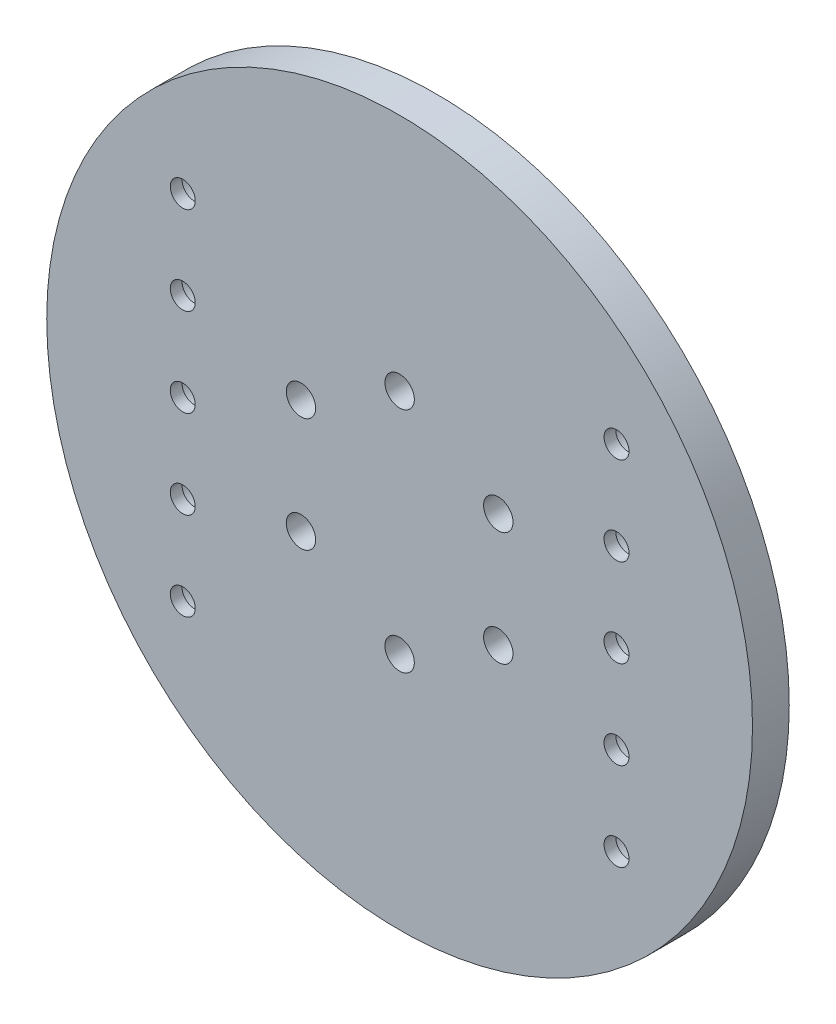
SolidWorks part; units mm, degrees
other "標示1"
sketch "草圖6" plane through (48, -48, 0) normal (0.0015, -0.0177, -0.9998) x (-1, 0.0075, -0.0016)
ref_plane "前基準面" through (0, 0, 0) normal (0, 0, 1) x (1, 0, 0)
ref_plane "上基準面" through (0, 0, 0) normal (0, 1, 0) x (1, 0, 0)
ref_plane "右基準面" through (0, 0, 0) normal (1, 0, 0) x (0, 0, -1)
sketch "草圖1" plane through (0, 0, 0) normal (0, 0, 1) x (1, 0, 0)
  circle A0 centre (0, 0) radius 48
  dimension "D1" = 96
extrude "填料-伸長1" add sketch "草圖1" along normal blind 5
sketch "草圖3" plane through (0, 0, 0) normal (0, 0, -1) x (-1, 0, 0)
  line L0 (-48, 0) -> (48, 0) construction
  line L1 (27, 27.5) -> (27, -27.5)
  line L2 (32, 27.5) -> (27, 27.5)
  line L3 (32, 27.5) -> (32, -27.5)
  line L4 (32, -27.5) -> (27, -27.5)
  line L9 (0, -48) -> (0, 48) construction
  line L14 (29.5, 27.5) -> (29.5, -27.5) construction
  line L15 (-32, -27.5) -> (-27, -27.5)
  line L16 (-32, 27.5) -> (-27, 27.5)
  line L17 (-27, 27.5) -> (-27, -27.5)
  line L18 (-32, 27.5) -> (-32, -27.5)
  circle A0 centre (0, 0) radius 48 construction
  circle A1 centre (29.5, 24) radius 1.25
  circle A2 centre (29.5, 12) radius 1.25
  circle A3 centre (29.5, 0) radius 1.25
  circle A4 centre (29.5, -12) radius 1.25
  circle A5 centre (29.5, -24) radius 1.25
  circle A6 centre (-29.5, 12) radius 1.25
  circle A7 centre (-29.5, 0) radius 1.25
  circle A8 centre (-29.5, -12) radius 1.25
  circle A9 centre (-29.5, -24) radius 1.25
  circle A10 centre (-29.5, 24) radius 1.25
  dimension "D6" = 2.5
  dimension "D8" = 12
  dimension "D1" = 27.5
  dimension "D2" = 5
  dimension "D3" = 3.5
  dimension "D4" = 27.5
  dimension "D5" = 27
  dimension "D7" = 5
hole_wizard "M3 六角承窩頭蓋螺釘的柱孔1" positions "3D草圖2" profile "草圖4" counterbore size "M3" standard "ISO" end condition through all
sketch3d "3D草圖2"
  point P0 (-29.5, 24, 0)
  point P3 (-29.5, 12, 0)
  point P6 (-29.5, 0, 0)
  point P9 (-29.5, -12, 0)
  point P12 (-29.5, -24, 0)
  point P15 (29.5, 24, 0)
  point P18 (29.5, 12, 0)
  point P21 (29.5, 0, 0)
  point P24 (29.5, -12, 0)
  point P27 (29.5, -24, 0)
sketch "草圖4" plane through (-29.5, 24, 0) normal (1, 0, 0) x (0, 1, 0)
  line L0 (0, 0) -> (0, 5)
  line L1 (0, 5) -> (1.7, 5)
  line L3 (1.7, 5) -> (1.7, 3.4)
  line L4 (3.25, 3.4) -> (1.7, 3.4)
  line L5 (3.25, 3.4) -> (3.25, 0.025)
  line L6 (3.25, 0.025) -> (3.275, 0)
  line L7 (3.275, 0) -> (0, 0)
  line L8 (-3.25, 0.025) -> (-3.275, 0) construction
  line L11 (0, -6.35) -> (0, 107.95) construction
  dimension "貫穿孔直徑" = 3.4
  dimension "貫穿孔深度" = 5
  dimension "柱孔直徑" = 6.5
  dimension "柱孔深度" = 3.4
  dimension "近端錐孔直徑" = 6.55
  dimension "近端錐孔角度" = 90
sketch "草圖5" plane through (0, 0, 0) normal (0, 0, -1) x (-1, 0, 0)
  circle A0 centre (0, 15.5) radius 2
  dimension "D1" = 4
  dimension "D2" = 15.5
extrude "除料-伸長1" cut sketch "草圖5" against normal up to next
pattern_circular "環狀複製排列1" count 6 over 360 about axis through (0, 0, 0) along (0, 0, 1) of "除料-伸長1"
